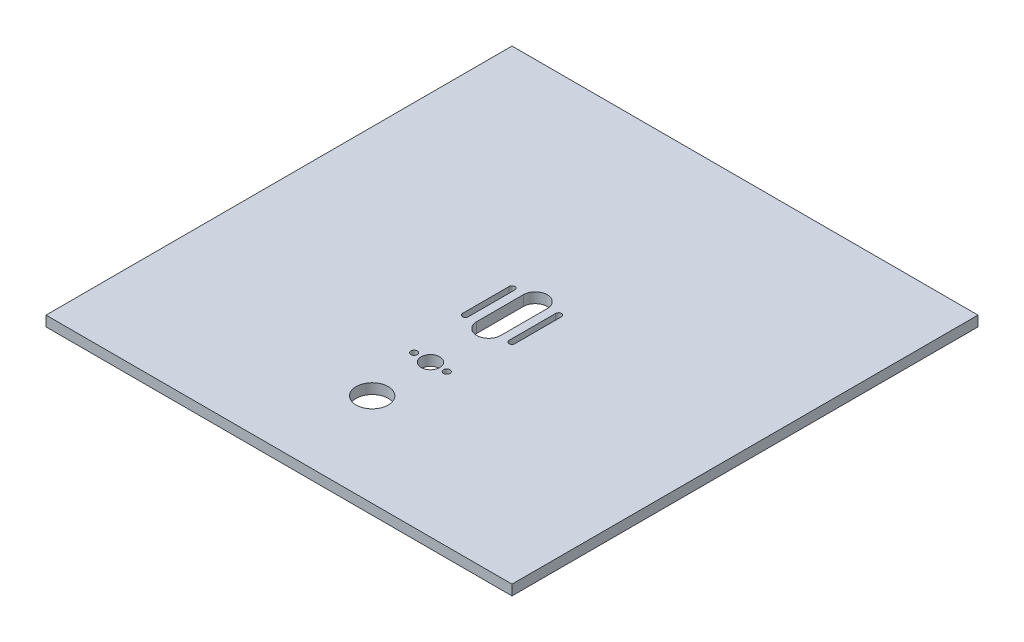
SolidWorks part; units mm, degrees
ref_plane "Front Plane" through (0, 0, 0) normal (0, 0, 1) x (1, 0, 0)
ref_plane "Top Plane" through (0, 0, 0) normal (0, 1, 0) x (1, 0, 0)
ref_plane "Right Plane" through (0, 0, 0) normal (1, 0, 0) x (0, 0, -1)
sketch "Sketch1" plane through (0, 0, 0) normal (0, 1, 0) x (1, 0, 0)
  line L1 (-127, -127) -> (127, -127)
  line L2 (-127, -127) -> (-127, 127)
  line L3 (-127, 127) -> (127, 127)
  line L4 (127, -127) -> (127, 127)
  line L5 (-127, -127) -> (127, 127) construction
  line L6 (-127, 127) -> (127, -127) construction
  point P0 (0, 0)
  dimension "D1" = 254
  dimension "D2" = 254
extrude "Boss-Extrude1" add sketch "Sketch1" along normal blind 5.588
sketch "Sketch2" plane through (0, 5.588, 0) normal (0, 1, 0) x (1, 0, 0)
  line L0 (-8.89, -44.45) -> (8.89, -44.45) construction
  line L1 (0, -76.2) -> (0, 0) construction
  line L2 (0, 12.7) -> (0, -12.7) construction
  line L3 (6.5405, 12.7) -> (6.5405, -12.7)
  line L4 (-6.5405, 12.7) -> (-6.5405, -12.7)
  line L5 (-12.7, 12.7) -> (-12.7, -12.7) construction
  line L6 (-12.7, -12.7) -> (12.7, -12.7) construction
  line L7 (-12.7, -12.7) -> (-12.7, 12.7) construction
  line L8 (-12.7, 12.7) -> (12.7, 12.7) construction
  line L9 (12.7, -12.7) -> (12.7, 12.7) construction
  line L10 (-12.7, -12.7) -> (12.7, 12.7) construction
  line L11 (-12.7, 12.7) -> (12.7, -12.7) construction
  line L12 (-11.1125, 12.7) -> (-11.1125, -12.7)
  line L13 (-14.2875, 12.7) -> (-14.2875, -12.7)
  line L14 (12.7, 12.7) -> (12.7, -12.7) construction
  line L15 (14.2875, 12.7) -> (14.2875, -12.7)
  line L16 (11.1125, 12.7) -> (11.1125, -12.7)
  circle A0 centre (0, -76.2) radius 8.7313
  circle A1 centre (0, -44.45) radius 5.08
  circle A2 centre (-8.89, -44.45) radius 1.778
  circle A3 centre (8.89, -44.45) radius 1.778
  arc A4 (6.5405, 12.7) -> (-6.5405, 12.7) centre (0, 12.7) ccw
  arc A5 (-6.5405, -12.7) -> (6.5405, -12.7) centre (0, -12.7) ccw
  arc A6 (-11.1125, 12.7) -> (-14.2875, 12.7) centre (-12.7, 12.7) ccw
  arc A7 (-14.2875, -12.7) -> (-11.1125, -12.7) centre (-12.7, -12.7) ccw
  arc A8 (14.2875, 12.7) -> (11.1125, 12.7) centre (12.7, 12.7) ccw
  arc A9 (11.1125, -12.7) -> (14.2875, -12.7) centre (12.7, -12.7) ccw
  point P7 (0, -44.45)
  point P10 (0, 0)
  point P21 (-12.7, 0)
  point P26 (12.7, 0)
  dimension "D1" = 10.16
  dimension "D2" = 3.556
  dimension "D10" = 17.4625
  dimension "D3" = 8.89
  dimension "D4" = 31.75
  dimension "D5" = 13.081
  dimension "D6" = 3.175
  dimension "D7" = 25.4
  dimension "D8" = 44.45
  dimension "D9" = 25.4
extrude "Cut-Extrude1" cut sketch "Sketch2" against normal through all
